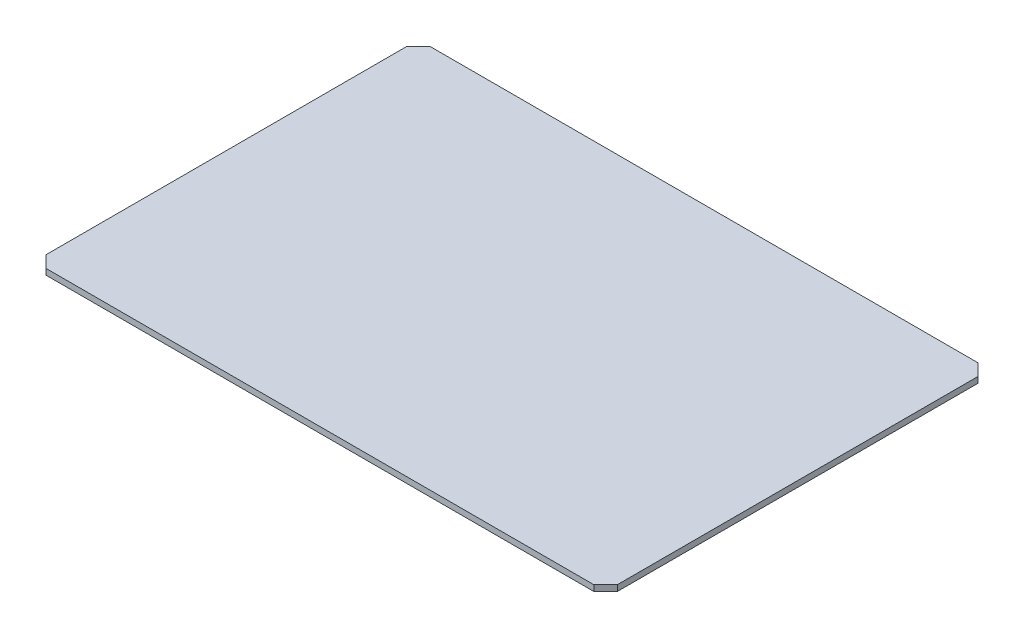
SolidWorks part; units mm, degrees
ref_plane "Front" through (0, 0, 0) normal (0, 0, 1) x (1, 0, 0)
ref_plane "Top" through (0, 0, 0) normal (0, 1, 0) x (1, 0, 0)
ref_plane "Right" through (0, 0, 0) normal (1, 0, 0) x (0, 0, -1)
sketch "Sketch1" plane through (0, 0, 0) normal (0, 1, 0) x (1, 0, 0)
  line L1 (0, 0) -> (290, 0)
  line L2 (0, 0) -> (0, 195)
  line L3 (0, 195) -> (290, 195)
  line L4 (290, 0) -> (290, 195)
  dimension "D1" = 290
  dimension "D2" = 195
extrude "Boss-Extrude1" add sketch "Sketch1" along normal blind 3
chamfer "Chamfer1" distance 6 angle 45 4 edges at (290, 1.5, -195) (0, 1.5, -195) (290, 1.5, 0) (0, 1.5, 0)
